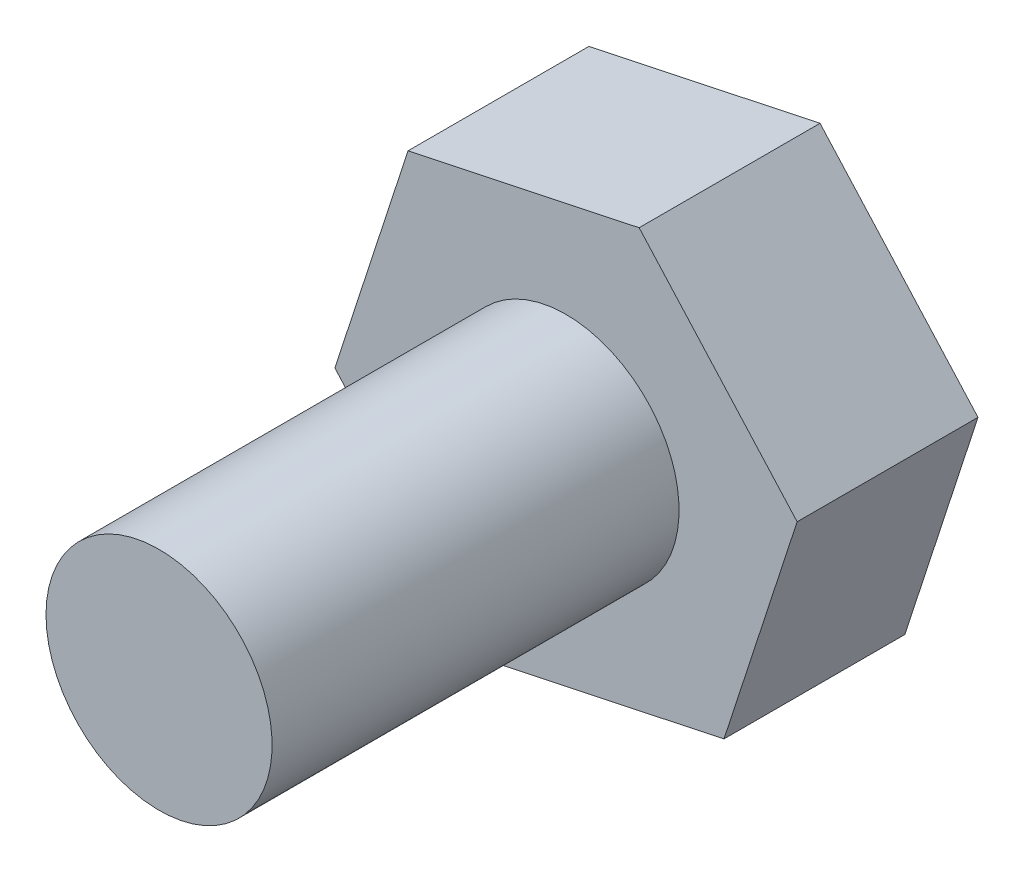
SolidWorks part; units mm, degrees
ref_plane "Front Plane" through (0, 0, 0) normal (0, 0, 1) x (1, 0, 0)
ref_plane "Top Plane" through (0, 0, 0) normal (0, 1, 0) x (1, 0, 0)
ref_plane "Right Plane" through (0, 0, 0) normal (1, 0, 0) x (0, 0, -1)
sketch "Sketch1" plane through (0, 0, 0) normal (0, 0, 1) x (1, 0, 0)
  line L1 (3.4939, -3.8851) -> (5.1116, 1.0832)
  line L2 (5.1116, 1.0832) -> (1.6177, 4.9683)
  line L3 (1.6177, 4.9683) -> (-3.4939, 3.8851)
  line L4 (-3.4939, 3.8851) -> (-5.1116, -1.0832)
  line L5 (-5.1116, -1.0832) -> (-1.6177, -4.9683)
  line L6 (-1.6177, -4.9683) -> (3.4939, -3.8851)
  circle A0 centre (0, 0) radius 2.5
  dimension "D1" = 2.5
extrude "Boss-Extrude3" add sketch "Sketch1" along normal blind 4
sketch "Sketch2" plane through (0, 0, 0) normal (0, 0, -1) x (-1, 0, 0)
  circle A0 centre (0, 0) radius 2.5
extrude "Boss-Extrude4" add sketch "Sketch2" against normal blind 13
